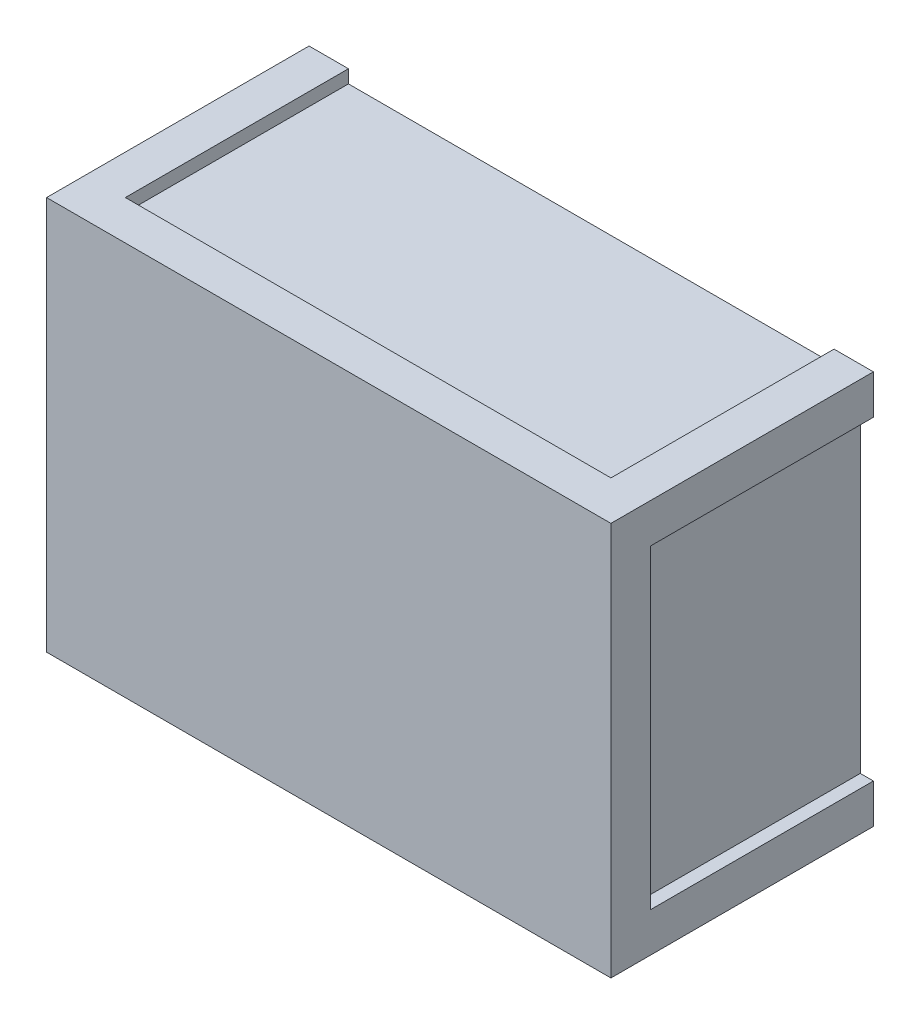
SolidWorks part; units mm, degrees
ref_plane "Front Plane" through (0, 0, 0) normal (0, 0, 1) x (1, 0, 0)
ref_plane "Top Plane" through (0, 0, 0) normal (0, 1, 0) x (1, 0, 0)
ref_plane "Right Plane" through (0, 0, 0) normal (1, 0, 0) x (0, 0, -1)
sketch "Sketch1" plane through (0, 0, 0) normal (0, 0, 1) x (1, 0, 0)
  line L1 (0, 0) -> (4500, 0)
  line L2 (0, 0) -> (0, 3200)
  line L3 (0, 3200) -> (4500, 3200)
  line L4 (4500, 0) -> (4500, 3200)
  line L5 (100, 100) -> (4400, 100)
  line L6 (100, 100) -> (100, 3100)
  line L7 (100, 3100) -> (4400, 3100)
  line L8 (4400, 100) -> (4400, 3100)
  dimension "D1" = 100
  dimension "D2" = 100
  dimension "D3" = 100
  dimension "D4" = 100
  dimension "D5" = 3000
  dimension "D6" = 4300
extrude "Boss-Extrude1" add sketch "Sketch1" along normal blind 2000
sketch "Sketch2" plane through (0, 3100, 0) normal (0, -1, 0) x (1, 0, 0)
  line L0 (4400, 0) -> (100, 0) construction
  line L1 (400, 0) -> (4100, 0)
  line L2 (400, 0) -> (400, 1700)
  line L3 (400, 1700) -> (4100, 1700)
  line L4 (4100, 0) -> (4100, 1700)
  line L5 (100, 2000) -> (100, 0) construction
  line L6 (4400, 2000) -> (4400, 0) construction
  line L7 (4400, 2000) -> (100, 2000) construction
  dimension "D1" = 300
  dimension "D2" = 300
  dimension "D3" = 300
extrude "Cut-Extrude1" cut sketch "Sketch2" against normal through all both and the other way through all
sketch "Sketch3" plane through (0, 0, 0) normal (-1, 0, 0) x (0, 0, 1)
  line L0 (2000, 100) -> (0, 100) construction
  line L1 (0, 400) -> (1700, 400)
  line L2 (0, 400) -> (0, 2800)
  line L3 (0, 2800) -> (1700, 2800)
  line L4 (1700, 400) -> (1700, 2800)
  line L5 (2000, 3100) -> (0, 3100) construction
  line L6 (2000, 3100) -> (2000, 100) construction
  line L7 (0, 3200) -> (0, 0) construction
  dimension "D1" = 300
  dimension "D2" = 300
  dimension "D3" = 300
extrude "Cut-Extrude2" cut sketch "Sketch3" against normal through all both and the other way through all
sketch "Sketch4" plane through (0, 0, 1700) normal (0, 0, -1) x (-1, 0, 0)
  line L0 (-400, 100) -> (-400, 0) construction
  line L1 (-4100, 0) -> (-400, 0)
  line L2 (-4100, 0) -> (-4100, 200)
  line L3 (-4100, 200) -> (-400, 200)
  line L4 (-400, 0) -> (-400, 200)
  line L5 (0, 400) -> (-200, 400)
  line L6 (0, 400) -> (0, 2800)
  line L7 (0, 2800) -> (-200, 2800)
  line L8 (-200, 400) -> (-200, 2800)
  line L9 (-400, 3200) -> (-4100, 3200)
  line L10 (-400, 3200) -> (-400, 3000)
  line L11 (-400, 3000) -> (-4100, 3000)
  line L12 (-4100, 3200) -> (-4100, 3000)
  line L13 (-4500, 400) -> (-4300, 400)
  line L14 (-4500, 400) -> (-4500, 2800)
  line L15 (-4500, 2800) -> (-4300, 2800)
  line L16 (-4300, 400) -> (-4300, 2800)
  line L17 (-100, 2800) -> (0, 2800) construction
  line L18 (-4100, 3200) -> (-4100, 3100) construction
  line L19 (-4500, 2800) -> (-4400, 2800) construction
  dimension "D1" = 200
  dimension "D2" = 200
  dimension "D3" = 200
  dimension "D4" = 200
extrude "Boss-Extrude2" add sketch "Sketch4" along normal up to surface (1700 mm away) separate body up to face at (4333.3333, 166.6667, 0)
sketch "Sketch5" plane through (0, 0, 2000) normal (0, 0, 1) x (1, 0, 0)
  line L1 (4400, 100) -> (100, 100)
  line L2 (4400, 100) -> (4400, 3100)
  line L3 (4400, 3100) -> (100, 3100)
  line L4 (100, 100) -> (100, 3100)
extrude "Boss-Extrude3" add sketch "Sketch5" against normal up to surface (2000 mm away) separate body up to face at (166.6667, 3033.3333, 0)
combine bodies "Combine1" operation type subtract main body 108 bodies to subtract 103 107 106 105 104
